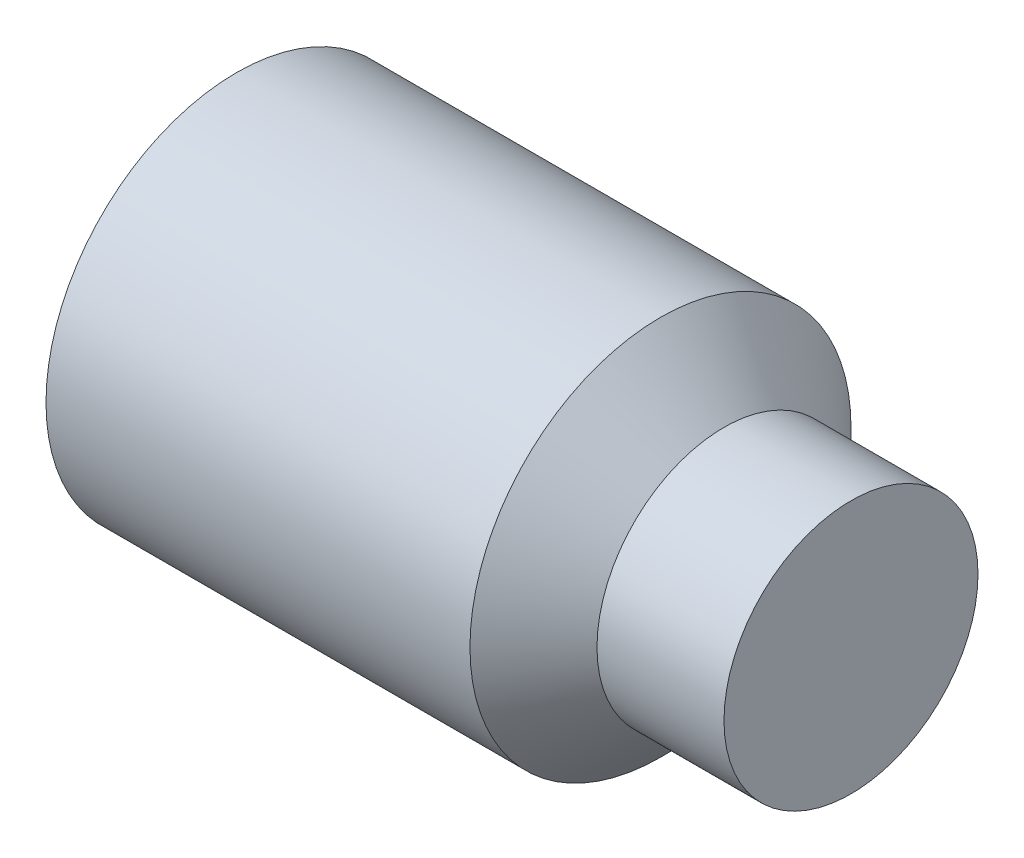
SolidWorks part; units mm, degrees
revolve "BaseBody" add sketch "BodySke" angle 360 about L5
sketch "BodySke" plane through (0, 0, 0) normal (0, 0, 1) x (1, 0, 0)
  line L0 (0, 0) -> (0, 1.2195)
  line L1 (0, 1.2195) -> (0.1619, 1.5)
  line L2 (0.1619, 1.5) -> (3.5, 1.5)
  line L3 (3.5, 1.5) -> (4, 1)
  line L4 (5, 0) -> (0, 0)
  line L5 (-12.7, 0) -> (88.9, 0) construction
  line L6 (4, 1) -> (5, 1)
  line L7 (5, 1) -> (5, 0)
  line L8 (0, -1.2195) -> (0.1619, -1.5) construction
  line L9 (4, -1) -> (5, -1) construction
  line L10 (0.25, 15.875) -> (0.25, -3.175) construction
  dimension "Diameter" = 3
  dimension "Drive_ch_ang" = 60
  dimension "Minor_dia" = 2.439
  dimension "Dog_dia" = 2
  dimension "Dog_len" = 1
  dimension "Length" = 5
  dimension "D1" = 45
  dimension "Advance" = 0.5
cosmetic thread "ThreadCosmetic" [suppressed] parameters "Thread_minor"=2.439
material "1.4301 (X5CrNi18-10)"
ref_plane "Plane1" through (0, 0, 0) normal (0, 0, 1) x (1, 0, 0)
ref_plane "Plane2" through (0, 0, 0) normal (0, 1, 0) x (1, 0, 0)
ref_plane "Plane3" through (0, 0, 0) normal (1, 0, 0) x (0, 0, -1)
other "Configuration Table"
sketch "Sketch2" plane through (0, 0, 0) normal (-1, 0, 0) x (0, 0, 1)
  line L0 (0.433, 0.75) -> (-0.433, 0.75)
  line L1 (-0.433, 0.75) -> (-0.866, 0)
  line L2 (0.433, 0.75) -> (0.866, 0)
  line L3 (0.433, -0.75) -> (0.866, 0)
  line L4 (0.433, -0.75) -> (-0.433, -0.75)
  line L5 (-0.433, -0.75) -> (-0.866, 0)
  dimension "Hex_size" = 1.5
  dimension "D2" = 0.75
  dimension "D3" = 0.75
extrude "Hex" cut sketch "Sketch2" against normal blind 1.2
sketch "ThdSchSke" plane through (0, 0, 0) normal (0, 0, 1) x (1, 0, 0)
  line L0 (0.1619, -1.2195) -> (-0.0345, -1.5)
  line L1 (0.1619, -1.2195) -> (0.3584, -1.5)
  line L2 (0.3584, -1.5) -> (0.3584, -1.875)
  line L3 (-3.175, 0) -> (5.1513, 0) construction
  line L4 (0.1619, 1.5) -> (0.1619, -1.5) construction
  line L5 (0.3584, -1.875) -> (-0.0345, -1.875)
  line L6 (-0.0345, -1.875) -> (-0.0345, -1.5)
  dimension "Thread_minor" = 2.439
  dimension "Diameter" = 3
revolve "ThreadSchematic" [suppressed] cut sketch "ThdSchSke" angle 360 about L3
pattern_linear "ThdSchPat" [suppressed]
equation "\"D2@Sketch2\" = \"Hex_size@Sketch2\" / 2"
equation "\"D3@Sketch2\" = \"Hex_size@Sketch2\" / 2"
equation "\"Thread_minor@ThreadCosmetic\" = \"Minor_dia@BodySke\""
equation "\"Thread_minor@ThdSchSke\" = \"Thread_minor@ThreadCosmetic\""
equation "\"Diameter@ThdSchSke\" = \"Diameter@BodySke\""
equation "\"Overcut@ThdSchSke\" = \"Diameter@BodySke\" * 1.25"
equation "\"Num_threads@ThdSchPat\" = int( (\"Length@BodySke\" - ( ( ( \"Diameter@BodySke\" - \"Minor_dia@BodySke\" ) * 0.5 ) / tan( \"Drive_ch_ang@BodySke\" * 0.017453292 ) ) - \"Dog_len@BodySke\" ) / \"Advance@BodySke\" + 0.999 )  + 1"
equation "\"Advance@ThdSchPat\" = (\"Length@BodySke\" - ( ( ( \"Diameter@BodySke\" - \"Minor_dia@BodySke\" ) * 0.5 ) / tan( \"Drive_ch_ang@BodySke\" * 0.017453292 ) ) - \"Dog_len@BodySke\" ) /  (\"Num_threads@ThdSchPat\" - 1) 'relax it"
equation "\"Num_threads@ThdSchPat\" = \"Num_threads@ThdSchPat\" - sgn( \"Num_threads@ThdSchPat\" - 1) '---chamfered tips only---"
